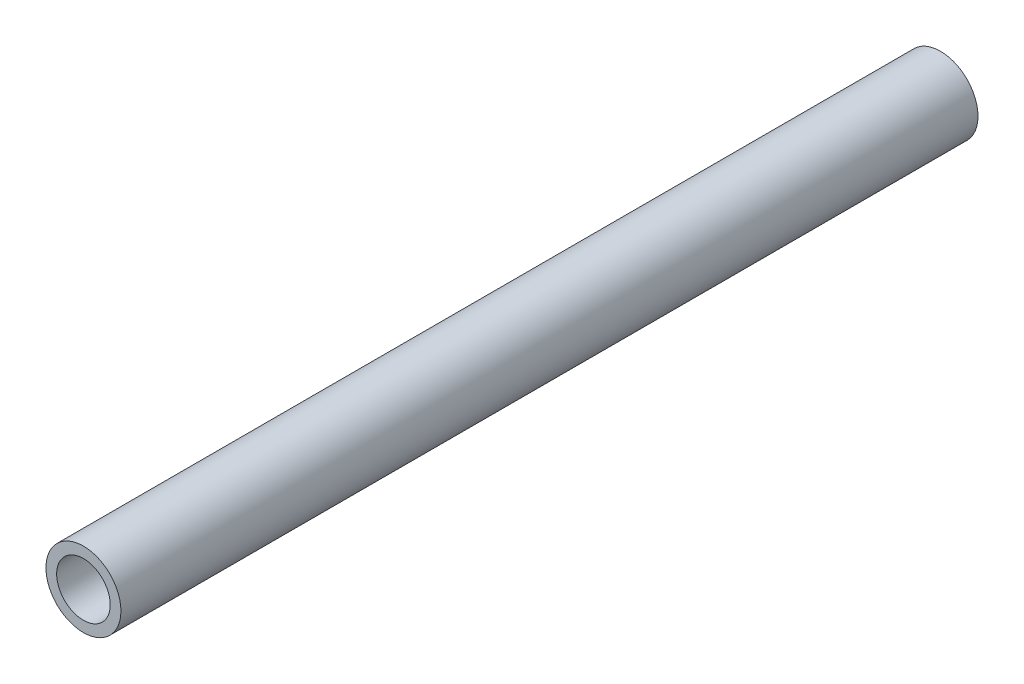
SolidWorks part; units mm, degrees
ref_plane "Front Plane" through (0, 0, 0) normal (0, 0, 1) x (1, 0, 0)
ref_plane "Top Plane" through (0, 0, 0) normal (0, 1, 0) x (1, 0, 0)
ref_plane "Right Plane" through (0, 0, 0) normal (1, 0, 0) x (0, 0, -1)
sketch "Sketch1" plane through (0, 0, 0) normal (0, 0, 1) x (1, 0, 0)
  line L1 (-19.9686, 464.2536) -> (19.9686, 464.2536) construction
  line L2 (0, 464.2536) -> (0, 457.2536) construction
  circle A0 centre (0, 457.2536) radius 3.5
  circle A1 centre (0, 457.2536) radius 2.5
  dimension "D1" = 7
  dimension "D2" = 1
extrude "Boss-Extrude1" add sketch "Sketch1" against normal blind 80
